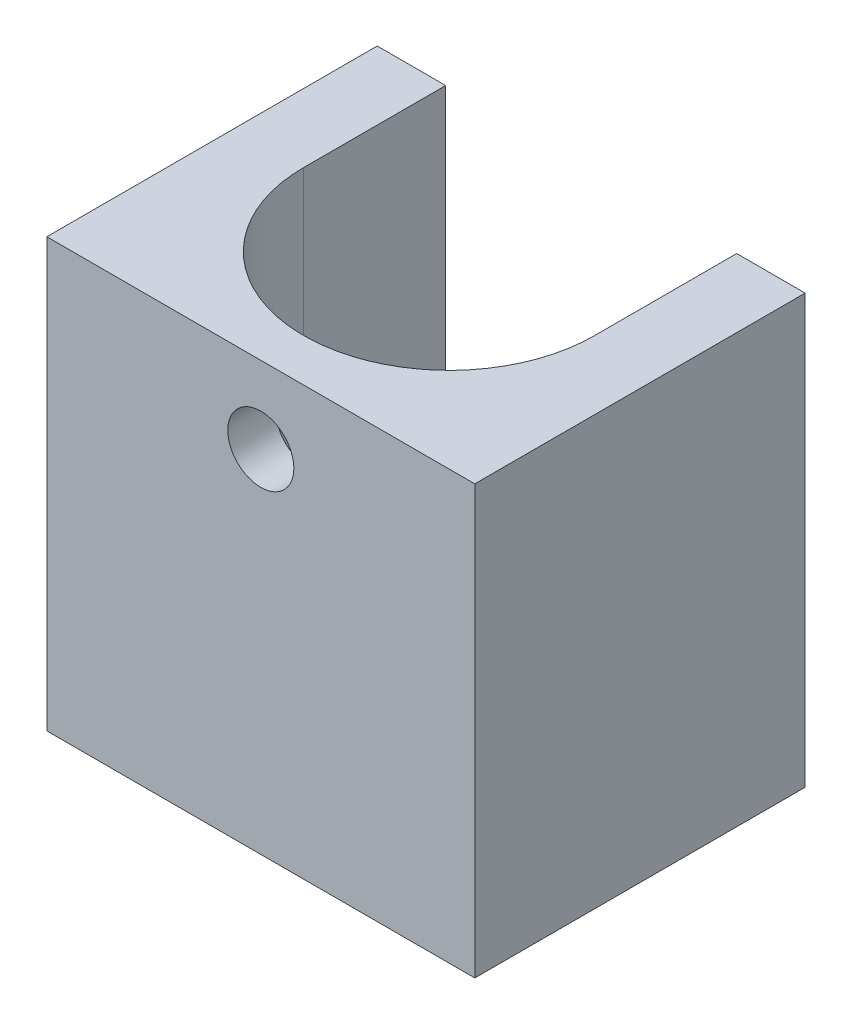
SolidWorks part; units mm, degrees
ref_plane "Front Plane" through (0, 0, 0) normal (0, 0, 1) x (1, 0, 0)
ref_plane "Top Plane" through (0, 0, 0) normal (0, 1, 0) x (1, 0, 0)
ref_plane "Right Plane" through (0, 0, 0) normal (1, 0, 0) x (0, 0, -1)
sketch "Sketch1" plane through (0, 0, 0) normal (0, 1, 0) x (1, 0, 0)
  line L1 (-15.875, -1.5875) -> (15.875, -1.5875)
  line L2 (-15.875, -1.5875) -> (-15.875, 1.5875)
  line L3 (-15.875, 1.5875) -> (15.875, 1.5875)
  line L4 (15.875, -1.5875) -> (15.875, 1.5875)
  line L5 (-15.875, -1.5875) -> (15.875, 1.5875) construction
  line L6 (-15.875, 1.5875) -> (15.875, -1.5875) construction
  point P0 (0, 0)
  dimension "D1" = 3.175
  dimension "D2" = 31.75
extrude "Boss-Extrude1" add sketch "Sketch1" along normal blind 31.75
sketch "Sketch2" plane through (0, 31.75, 0) normal (0, 1, 0) x (1, 0, 0)
  line L0 (15.875, -1.5875) -> (15.875, 1.5875) construction
  line L1 (15.875, 1.5875) -> (-15.875, 1.5875) construction
  line L2 (-15.875, 1.5875) -> (-15.875, 12.3825)
  line L3 (-10.795, 12.3825) -> (-15.875, 12.3825)
  line L4 (-15.875, 1.5875) -> (0, 1.5875)
  arc A0 (-10.795, 12.3825) -> (0, 1.5875) centre (0, 12.3825) ccw
  dimension "D2" = 21.59
  dimension "D1" = 15.875
extrude "Boss-Extrude2" add sketch "Sketch2" against normal blind 31.75
mirror "Mirror1" about plane through (0, 0, 0) normal (1, 0, 0) of "Boss-Extrude2"
sketch "Sketch3" plane through (0, 31.75, 0) normal (0, 1, 0) x (1, 0, 0)
  line L0 (-15.875, 12.3825) -> (-10.795, 12.3825)
  line L1 (-10.795, 12.3825) -> (-10.795, 22.9235)
  line L2 (-10.795, 22.9235) -> (-15.875, 22.9235)
  line L3 (-15.875, 22.9235) -> (-15.875, 12.3825)
  dimension "D1" = 10.541
extrude "Boss-Extrude3" add sketch "Sketch3" against normal blind 31.75
mirror "Mirror2" about plane through (0, 0, 0) normal (1, 0, 0) of "Boss-Extrude3"
sketch "Sketch4" plane through (0, 0, 1.5875) normal (0, 0, 1) x (1, 0, 0)
  line L0 (0, 0) -> (0, 31.75) construction
  line L1 (-15.875, 31.75) -> (15.875, 31.75) construction
  line L2 (5.204, 28.0912) -> (5.204, 26.035) construction
  line L3 (5.204, 26.035) -> (6.8861, 26.035) construction
  line L4 (5.204, 28.0912) -> (7.4117, 28.0912) construction
  circle A0 centre (0, 26.035) radius 2.4511
  circle A1 centre (0, 5.715) radius 2.3241
  point P7 (0, 15.875)
  dimension "D1" = 4.9022
  dimension "D4" = 4.6482
  dimension "D2" = 10.16
  dimension "D3" = 20.32
extrude "Cut-Extrude1" cut sketch "Sketch4" against normal blind 31.75
sketch "Sketch6" plane through (0, 0, 1.5875) normal (0, 0, 1) x (1, 0, 0)
  circle A0 centre (0, 5.715) radius 2.3241 construction
  circle A1 centre (0, 5.715) radius 2.3241
extrude "Boss-Extrude4" add sketch "Sketch6" against normal blind 15.875
fillet "Fillet1" radius 0.762 1 edges at (2.3241, 5.715, -14.2875)
